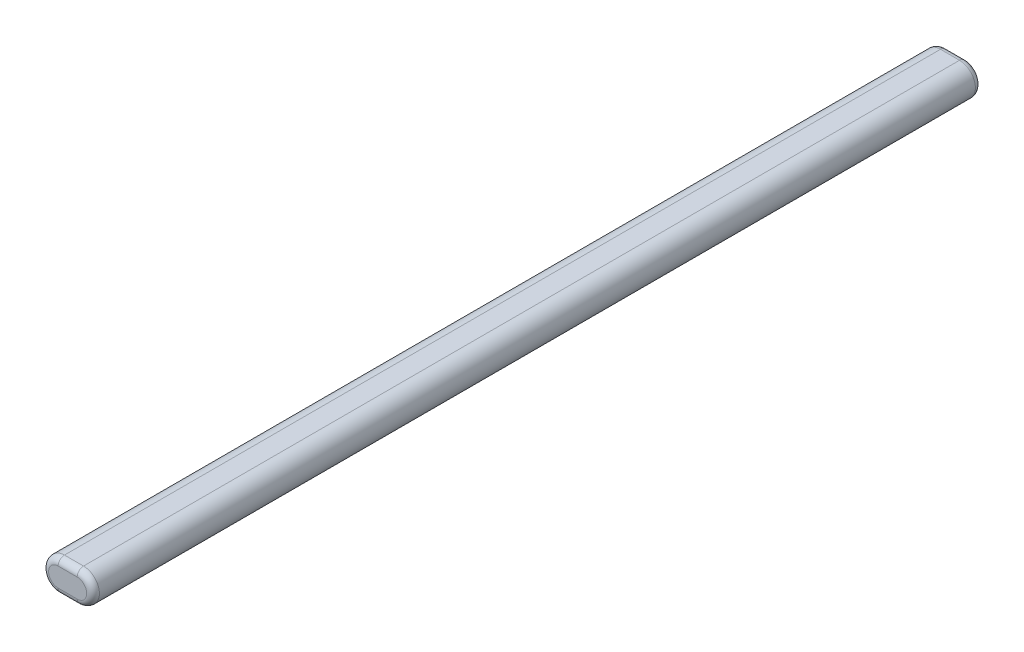
SolidWorks part; units mm, degrees
ref_plane "前基準面" through (0, 0, 0) normal (0, 0, 1) x (1, 0, 0)
ref_plane "上基準面" through (0, 0, 0) normal (0, 1, 0) x (1, 0, 0)
ref_plane "右基準面" through (0, 0, 0) normal (1, 0, 0) x (0, 0, -1)
sketch "草圖1" plane through (0, 0, 0) normal (0, 0, 1) x (1, 0, 0)
  line L0 (-7.5, 0) -> (7.5, 0) construction
  line L1 (-7.5, 12.5) -> (7.5, 12.5)
  line L2 (-7.5, -12.5) -> (7.5, -12.5)
  arc A0 (-7.5, 12.5) -> (-7.5, -12.5) centre (-7.5, 0) ccw
  arc A1 (7.5, -12.5) -> (7.5, 12.5) centre (7.5, 0) ccw
  point P2 (0, 0)
  dimension "D1" = 25
  dimension "D2" = 15
extrude "填料-伸長1" add sketch "草圖1" along normal blind 700
fillet "圓角1" radius 5 8 edges at (0, -12.5, 0) (-20, 0, 0) (0, 12.5, 0) (0, -12.5, 700) (-20, 0, 700) (0, 12.5, 700) (20, 0, 0) (20, 0, 700)
